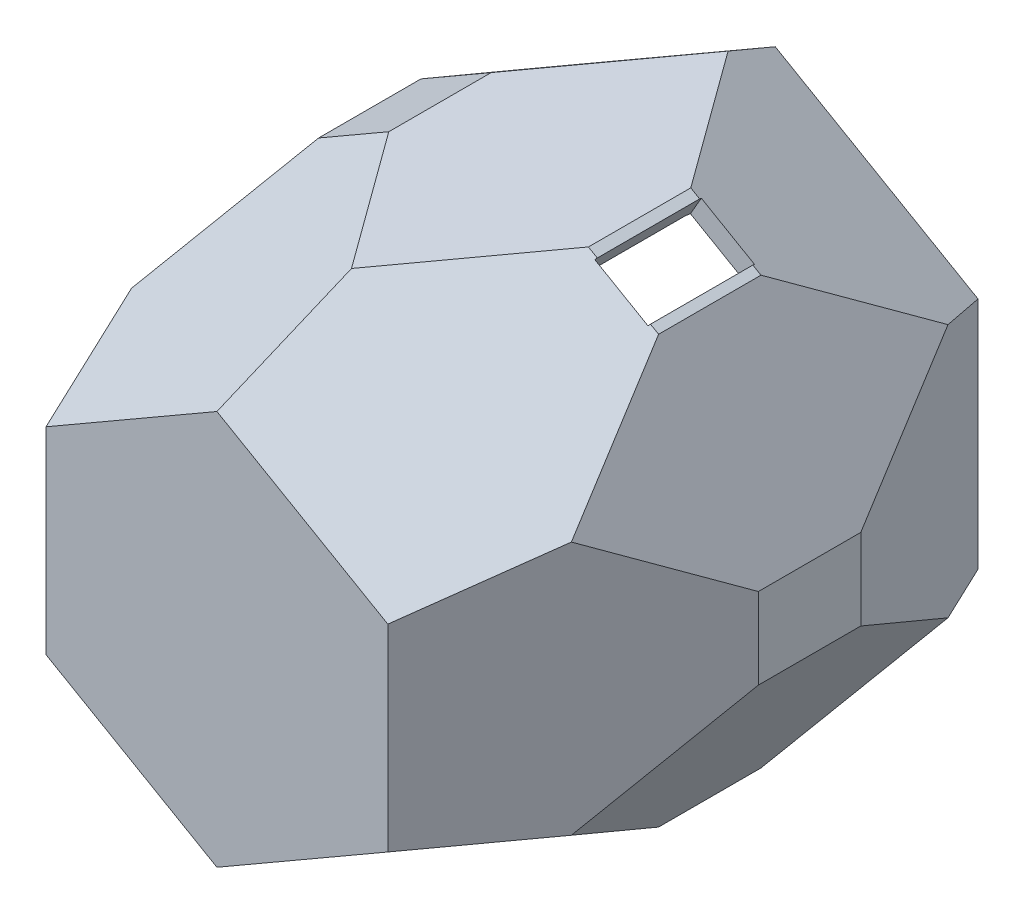
SolidWorks part; units mm, degrees
ref_plane "Front Plane" through (0, 0, 0) normal (0, 0, 1) x (1, 0, 0)
ref_plane "Top Plane" through (0, 0, 0) normal (0, 1, 0) x (1, 0, 0)
ref_plane "Right Plane" through (0, 0, 0) normal (1, 0, 0) x (0, 0, -1)
sketch "Sketch1" plane through (0, 0, 0) normal (0, 0, 1) x (1, 0, 0)
  line L1 (0, 57.1577) -> (-49.5, 28.5788)
  line L2 (-49.5, 28.5788) -> (-49.5, -28.5788)
  line L3 (-49.5, -28.5788) -> (0, -57.1577)
  line L4 (0, -57.1577) -> (49.5, -28.5788)
  line L5 (49.5, -28.5788) -> (49.5, 28.5788)
  line L6 (49.5, 28.5788) -> (0, 57.1577)
  circle A0 centre (0, 0) radius 49.5 construction
  dimension "D1" = 99
extrude "Boss-Extrude1" add sketch "Sketch1" along normal blind 45 draft 20 draft outward yes
sketch "Sketch3" plane through (0, 0, 45) normal (0, 0, 1) x (1, 0, 0)
  line L1 (0, -76.0701) -> (65.8787, -38.0351)
  line L2 (65.8787, -38.0351) -> (65.8787, 38.0351)
  line L3 (65.8787, 38.0351) -> (0, 76.0701)
  line L4 (0, 76.0701) -> (-65.8787, 38.0351)
  line L5 (-65.8787, 38.0351) -> (-65.8787, -38.0351)
  line L6 (-65.8787, -38.0351) -> (0, -76.0701)
  circle A0 centre (0, 0) radius 65.8787 construction
extrude "Boss-Extrude3" add sketch "Sketch3" along normal blind 25
sketch "Sketch4" plane through (0, 0, 70) normal (0, 0, 1) x (1, 0, 0)
  line L1 (65.8787, -38.0351) -> (65.8787, 38.0351)
  line L2 (65.8787, 38.0351) -> (0, 76.0701)
  line L3 (0, 76.0701) -> (-65.8787, 38.0351)
  line L4 (-65.8787, 38.0351) -> (-65.8787, -38.0351)
  line L5 (-65.8787, -38.0351) -> (0, -76.0701)
  line L6 (0, -76.0701) -> (65.8787, -38.0351)
  circle A0 centre (0, 0) radius 65.8787 construction
extrude "Boss-Extrude4" add sketch "Sketch4" along normal blind 66.34 draft 20
ref_plane "Plane1" through (0, 77, 0) normal (0, 1, 0) x (1, 0, 0)
sketch "Sketch5" plane through (0, 77, 0) normal (0, 1, 0) x (1, 0, 0)
  line L0 (0, 0) -> (-49.5, 0) construction
  line L1 (-30, 0) -> (30, 0)
  line L2 (-30, 0) -> (-30, -136.34)
  line L3 (-30, -136.34) -> (30, -136.34)
  line L4 (30, 0) -> (30, -136.34)
  line L5 (41.7329, -136.34) -> (0, -136.34) construction
  dimension "D1" = 30
  dimension "D2" = 60
extrude "Cut-Extrude4" cut sketch "Sketch5" against normal blind 15
pattern_circular "CirPattern1" count 6 over 360 about axis through (0, 0, 0) along (0, 0, 1) of "Cut-Extrude4"
shell "Shell1" thickness 5
sketch "Sketch6" plane through (32.9393, 57.0526, 0) normal (0.5, 0.866, 0) x (0.866, -0.5, 0)
  line L0 (-7.3948, -70.5) -> (-7.3948, -44.5)
  line L1 (-7.3948, -44.5) -> (7.6052, -44.5)
  line L2 (7.6052, -70.5) -> (-7.3948, -70.5)
  line L3 (7.6052, -44.5) -> (7.6052, -70.5)
  line L6 (9.8948, -45) -> (-9.8948, -45) construction
  point P10 (0, -45)
  dimension "D1" = 15
  dimension "D2" = 26
extrude "Cut-Extrude5" cut sketch "Sketch6" against normal blind 10
